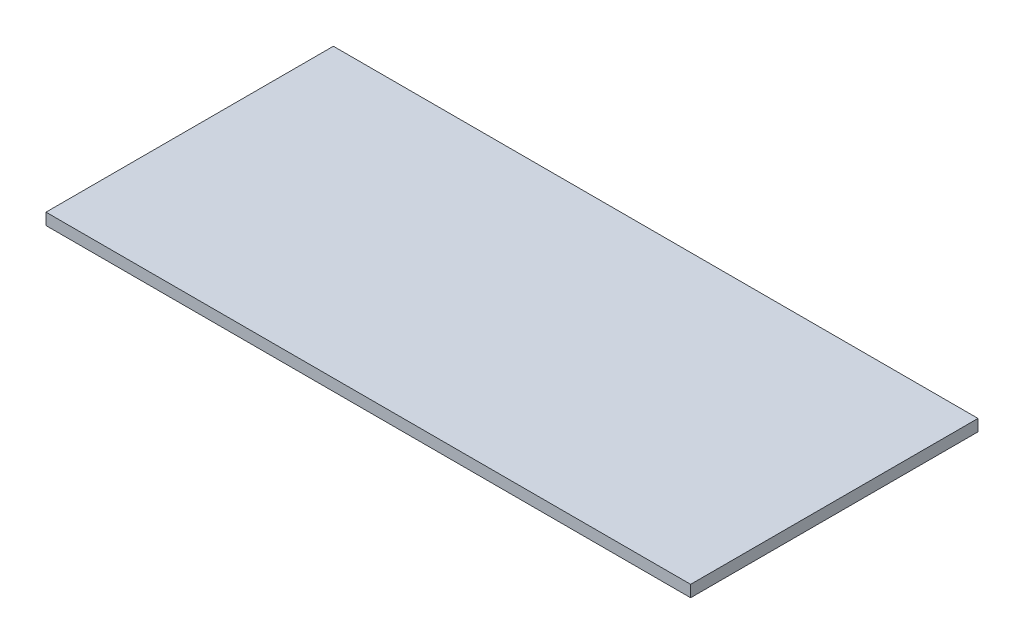
SolidWorks part; units mm, degrees
material "Oak"
ref_plane "Front" through (0, 0, 0) normal (0, 0, 1) x (1, 0, 0)
ref_plane "Top" through (0, 0, 0) normal (0, 1, 0) x (1, 0, 0)
ref_plane "Right" through (0, 0, 0) normal (1, 0, 0) x (0, 0, -1)
sketch "Sketch1" plane through (0, 914.4, 0) normal (0, 1, 0) x (1, 0, 0)
  line L1 (-19.05, 933.45) -> (1035.05, 933.45)
  line L2 (-19.05, 933.45) -> (-19.05, 463.55)
  line L3 (-19.05, 463.55) -> (1035.05, 463.55)
  line L4 (1035.05, 933.45) -> (1035.05, 463.55)
extrude "Boss-Extrude1" add sketch "Sketch1" along normal blind 19.05
equation "\"D1@Boss-Extrude1\" = \"MAT_THICKNESS@shapeoko_enclosure.Assembly\""
